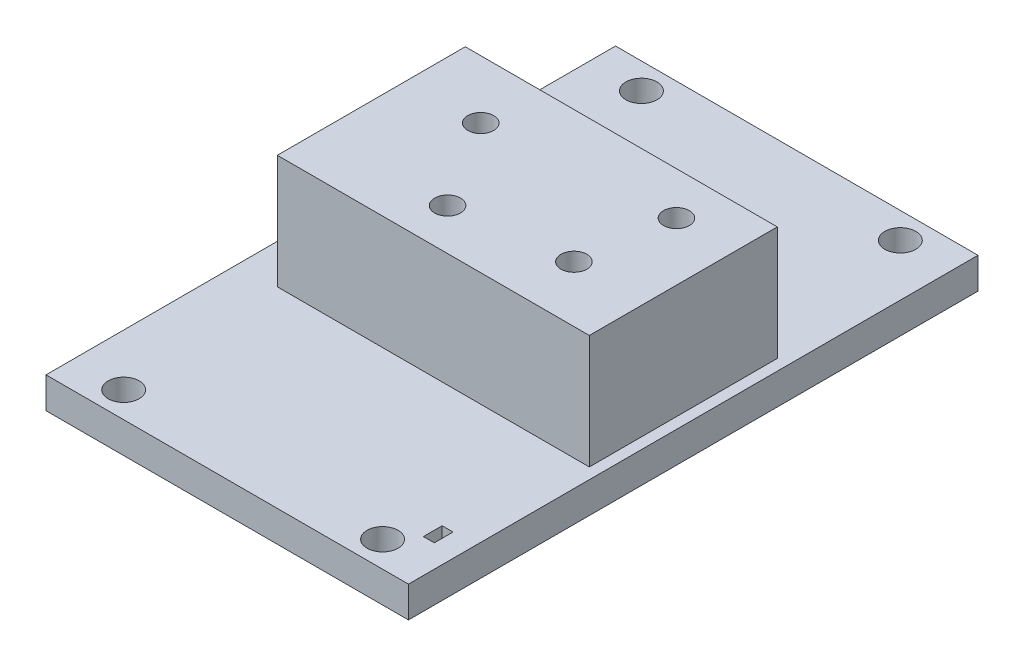
SolidWorks part; units mm, degrees
ref_plane "Front Plane" through (0, 0, 0) normal (0, 0, 1) x (1, 0, 0)
ref_plane "Top Plane" through (0, 0, 0) normal (0, 1, 0) x (1, 0, 0)
ref_plane "Right Plane" through (0, 0, 0) normal (1, 0, 0) x (0, 0, -1)
sketch "Sketch1" plane through (0, 0, 0) normal (0, 1, 0) x (1, 0, 0)
  line L0 (-12.5, 25) -> (12.5, -25) construction
  line L1 (-17.5, -27.5) -> (17.5, -27.5)
  line L2 (-17.5, -27.5) -> (-17.5, 27.5)
  line L3 (-17.5, 27.5) -> (17.5, 27.5)
  line L4 (17.5, -27.5) -> (17.5, 27.5)
  line L5 (17.5, 0) -> (-17.5, 0) construction
  line L6 (14.244, -20.9912) -> (15.2972, -20.9912)
  line L7 (-12.5, -25) -> (12.5, -25) construction
  line L8 (-12.5, -25) -> (-12.5, 25) construction
  line L9 (-12.5, 25) -> (12.5, 25) construction
  line L10 (12.5, -25) -> (12.5, 25) construction
  line L11 (14.244, -20.9912) -> (14.244, -22.8013)
  line L12 (14.244, -22.8013) -> (15.2972, -22.8013)
  line L13 (15.2972, -20.9912) -> (15.2972, -22.8013)
  line L14 (14.244, -20.9912) -> (15.2972, -22.8013) construction
  line L15 (14.244, -22.8013) -> (15.2972, -20.9912) construction
  circle A0 centre (12.5, 25) radius 1.5
  circle A1 centre (-12.5, 25) radius 1.5
  circle A2 centre (12.5, -25) radius 1.5
  circle A3 centre (-12.5, -25) radius 1.5
  circle A8 centre (-1.27, -4.95) radius 1.25
  circle A9 centre (-6.57, 3.55) radius 1.25
  circle A10 centre (10.83, 5.05) radius 1.25
  circle A11 centre (9.53, -3.55) radius 1.25
  point P0 (0, 0)
  point P6 (0, 0)
  point P25 (0, 27.5)
  point P26 (0, 25)
  point P27 (12.5, 0)
  point P28 (-17.5, 0)
  point P29 (14.7706, -21.8962)
  dimension "D3" = 3
  dimension "D11" = 2.5
  dimension "D1" = 25
  dimension "D2" = 50
  dimension "D4" = 11.23
  dimension "D6" = 8.5
  dimension "D7" = 1.3
  dimension "D8" = 10.8
  dimension "D9" = 20.05
  dimension "D10" = 8.6
  dimension "D12" = 17.4
  dimension "D13" = 35
  dimension "D14" = 55
  dimension "D15" = 1.4
extrude "Boss-Extrude1" add sketch "Sketch1" along normal blind 3
sketch "Sketch2" plane through (0, 3, 0) normal (0, 1, 0) x (1, 0, 0)
  line L1 (-13.6936, 9.1821) -> (16.4369, 9.1821)
  line L2 (-13.6936, 9.1821) -> (-13.6936, -8.9691)
  line L3 (-13.6936, -8.9691) -> (16.4369, -8.9691)
  line L4 (16.4369, 9.1821) -> (16.4369, -8.9691)
extrude "Boss-Extrude2" add sketch "Sketch2" along normal blind 11
sketch "Sketch3" plane through (0, 3, 0) normal (0, -1, 0) x (1, 0, 0)
  circle A6 centre (-1.27, 4.95) radius 1.25
  circle A7 centre (-6.57, -3.55) radius 1.25
  circle A8 centre (9.53, 3.55) radius 1.25
  circle A9 centre (10.83, -5.05) radius 1.25
extrude "Cut-Extrude1" cut sketch "Sketch3" against normal through all
sketch "Sketch4" plane through (0, 0, 0) normal (0, -1, 0) x (1, 0, 0)
  line L1 (14.2012, 8.8296) -> (-11.7715, 8.8296)
  line L2 (14.2012, 8.8296) -> (14.2012, -8.906)
  line L3 (14.2012, -8.906) -> (-11.7715, -8.906)
  line L4 (-11.7715, 8.8296) -> (-11.7715, -8.906)
extrude "Cut-Extrude2" cut sketch "Sketch4" against normal blind 4
